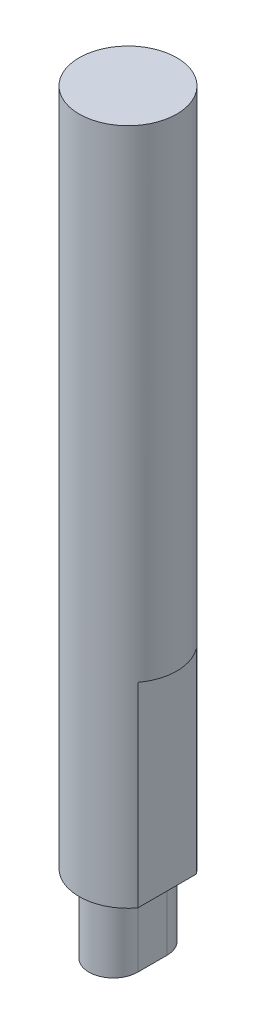
SolidWorks part; units mm, degrees
ref_plane "Front Plane" through (0, 0, 0) normal (0, 0, 1) x (1, 0, 0)
ref_plane "Top Plane" through (0, 0, 0) normal (0, 1, 0) x (1, 0, 0)
ref_plane "Right Plane" through (0, 0, 0) normal (1, 0, 0) x (0, 0, -1)
sketch "Sketch1" plane through (0, 0, 0) normal (0, 1, 0) x (1, 0, 0)
  circle A0 centre (0, 0) radius 2.5
  dimension "D1" = 5
extrude "Boss-Extrude1" add sketch "Sketch1" along normal blind 50
sketch "Sketch2" plane through (0, 0, 0) normal (0, -1, 0) x (-1, 0, 0)
  circle A0 centre (0, 0) radius 2.5
extrude "Boss-Extrude2" add sketch "Sketch2" along normal up to surface (8.2955 mm away)
sketch "Sketch4" plane through (0, -8.2955, 0) normal (0, -1, 0) x (1, 0, 0)
  line L0 (0, 0.75) -> (0, -0.75) construction
  line L1 (1.25, 0.75) -> (1.25, -0.75)
  line L2 (-1.25, 0.75) -> (-1.25, -0.75)
  arc A0 (1.25, 0.75) -> (-1.25, 0.75) centre (0, 0.75) ccw
  arc A1 (-1.25, -0.75) -> (1.25, -0.75) centre (0, -0.75) ccw
  point P3 (0, 0)
  dimension "D2" = 1.25
  dimension "D1" = 1.5
extrude "Cut-Extrude1" cut sketch "Sketch4" against normal blind 3.6 flip side to cut
sketch "Sketch5" plane through (0, -4.6955, 0) normal (0, -1, 0) x (-1, 0, 0)
  line L0 (2, -1.5) -> (2, 1.5)
  line L1 (-2, -1.5) -> (-2, 1.5)
  circle A0 centre (0, 0) radius 2.5 construction
  arc A1 (2, -1.5) -> (2, 1.5) centre (0, 0) ccw
  arc A2 (-2, -1.5) -> (-2, 1.5) centre (0, 0) cw
  dimension "D1" = 2
  dimension "D2" = 2
extrude "Cut-Extrude2" cut sketch "Sketch5" against normal blind 10
sketch "Sketch7" plane through (0, 50, 0) normal (0, 1, 0) x (1, 0, 0)
  circle A0 centre (0, 0) radius 2.5
  dimension "D1" = 5
extrude "Cut-Extrude3" cut sketch "Sketch7" against normal blind 20
